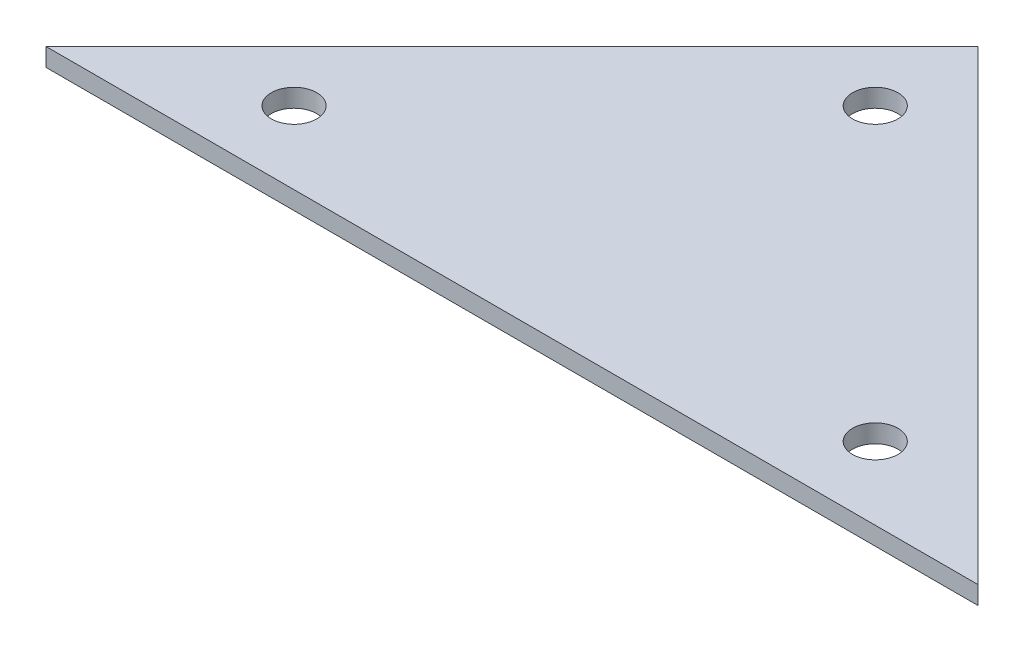
SolidWorks part; units mm, degrees
ref_plane "Front Plane" through (0, 0, 0) normal (0, 0, 1) x (1, 0, 0)
ref_plane "Top Plane" through (0, 0, 0) normal (0, 1, 0) x (1, 0, 0)
ref_plane "Right Plane" through (0, 0, 0) normal (1, 0, 0) x (0, 0, -1)
sketch "Sketch1" plane through (0, 0, 0) normal (0, 1, 0) x (1, 0, 0)
  line L0 (0, 68.7605) -> (-81.4605, -12.7)
  line L1 (-81.4605, -12.7) -> (81.4605, -12.7)
  line L2 (81.4605, -12.7) -> (0, 68.7605)
  line L3 (-55, 0) -> (55, 0) construction
  line L4 (0, -55) -> (0, 55) construction
  circle A0 centre (-50.8, 0) radius 3.9687
  circle A1 centre (0, 50.8) radius 3.9688
  circle A2 centre (50.8, 0) radius 3.9687
  dimension "D4" = 7.9375
  dimension "D1" = 50.8
  dimension "D2" = 50.8
  dimension "D3" = 50.8
  dimension "D5" = 12.7
  dimension "D6" = 12.7
  dimension "D7" = 12.7
  dimension "D8" = 12.7
  dimension "D9" = 12.7
extrude "Boss-Extrude1" add sketch "Sketch1" along normal mid plane 3.175
